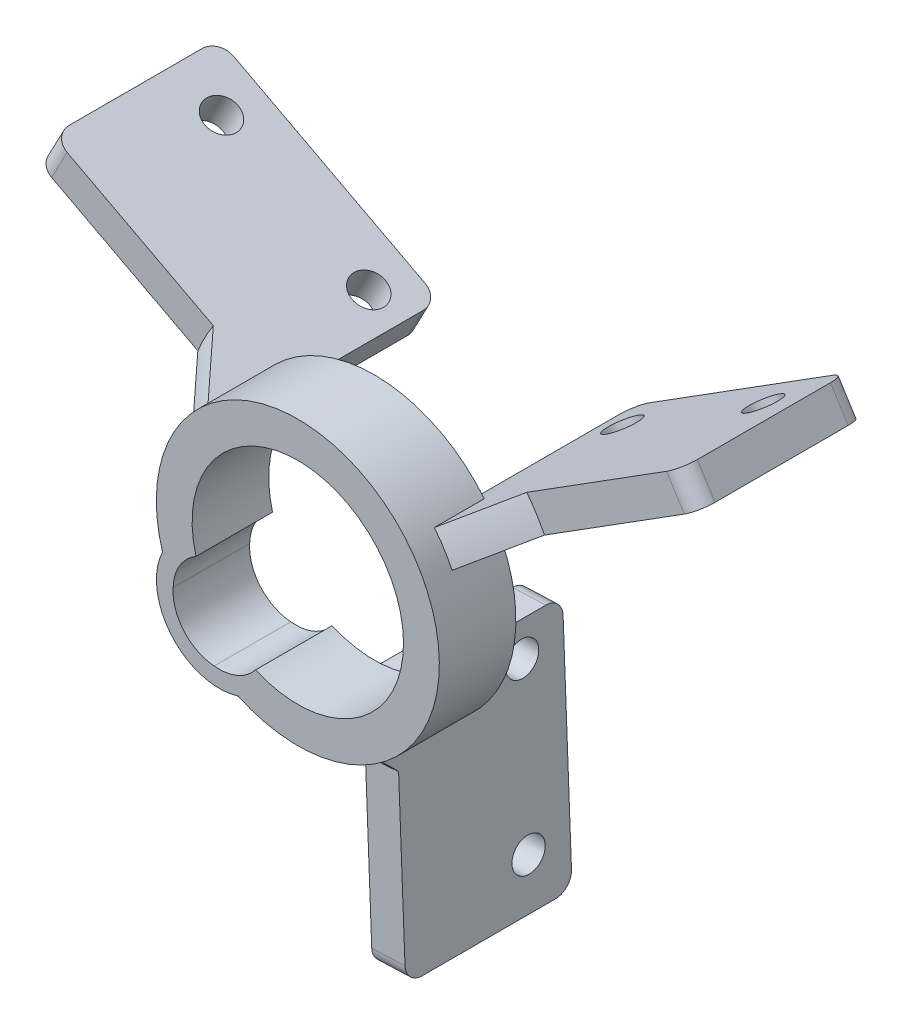
SolidWorks part; units mm, degrees
ref_plane "Alzado" through (0, 0, 0) normal (0, 0, 1) x (1, 0, 0)
ref_plane "Planta" through (0, 0, 0) normal (0, 1, 0) x (1, 0, 0)
ref_plane "Vista lateral" through (0, 0, 0) normal (1, 0, 0) x (0, 0, -1)
sketch "Croquis1" plane through (0, 0, 0) normal (0, 0, 1) x (1, 0, 0)
  circle A1 centre (0, 0) radius 8.5
  dimension "D2" = 17
extrude "Saliente-Extruir1" add sketch "Croquis1" along normal blind 4.6
sketch "Croquis6" plane through (0, 0, 4.6) normal (0, 0, 1) x (1, 0, 0)
  circle A0 centre (0, 0) radius 6.35
  dimension "D1" = 12.7
extrude "Cortar-Extruir1" cut sketch "Croquis6" against normal through all
sketch "Croquis13" plane through (0, 0, 0) normal (0, 0, -1) x (-1, 0, 0)
  circle A0 centre (4.7169, -4.1004) radius 2.775
  circle A1 centre (0, 0) radius 6.35 construction
  arc A2 (1.5517, -6.1575) -> (6.3135, -0.6796) centre (4.7169, -4.1004) ccw
  arc A3 (1.5517, -6.1575) -> (6.3135, -0.6796) centre (0, 0) ccw
  dimension "D1" = 5.55
  dimension "D2" = 6.25
  dimension "D3" = 7.55
extrude "Cortar-Extruir7" cut sketch "Croquis13" against normal blind 10 contours A0
sketch "Croquis14" plane through (0, 0, 0) normal (0, 0, -1) x (-1, 0, 0)
  arc A0 (1.5517, -6.1575) -> (6.3135, -0.6796) centre (4.7169, -4.1004) ccw
  arc A1 (2.5392, -5.8202) -> (5.0208, -6.8587) centre (4.7169, -4.1004) ccw construction
  arc A3 (1.5517, -6.1575) -> (2.5392, -5.8202) centre (0, 0) ccw
  arc A4 (6.117, -1.7044) -> (2.5392, -5.8202) centre (0, 0) ccw construction
  arc A5 (2.5392, -5.8202) -> (5.0208, -6.8587) centre (4.7169, -4.1004) ccw
  arc A6 (6.3135, -0.6796) -> (6.117, -1.7044) centre (0, 0) cw
  arc A7 (6.117, -1.7044) -> (7.4907, -4.0174) centre (4.7169, -4.1004) cw
  arc A8 (7.4907, -4.0174) -> (5.0208, -6.8587) centre (4.8351, -4.2031) cw
  dimension "D1" = 7.55
  dimension "D2" = 0
extrude "Saliente-Extruir4" add sketch "Croquis14" against normal blind 4.6
sketch "Croquis15" plane through (0, 0, 0) normal (0, 0, -1) x (-1, 0, 0)
  line L0 (6.0679, 4.3151) -> (7, 2.5456)
  line L1 (7, 2.5456) -> (20.2714, 9.5363)
  line L2 (20.2714, 9.5363) -> (19.3393, 11.3059)
  line L3 (19.3393, 11.3059) -> (6.0679, 4.3151)
  line L4 (0.1215, -22.4012) -> (0.703, -7.4125)
  line L5 (0.703, -7.4125) -> (-1.2955, -7.335)
  line L6 (-1.2955, -7.335) -> (-1.877, -22.3237)
  line L7 (-1.877, -22.3237) -> (0.1215, -22.4012)
  line L8 (-19.4608, 11.0954) -> (-6.7709, 3.0974)
  line L9 (-6.7709, 3.0974) -> (-5.7045, 4.7894)
  line L10 (-5.7045, 4.7894) -> (-18.3944, 12.7873)
  line L11 (-18.3944, 12.7873) -> (-19.4608, 11.0954)
  point P16 (0, 0)
  dimension "D1" = 2
  dimension "D2" = 15
  dimension "D3" = 7
  dimension "D4" = 4.25
  dimension "D5" = 3
extrude "Saliente-Extruir6" add sketch "Croquis15" along normal blind 10
chamfer "Chaflán1" distance 3 angle 45 1 edges at (-7.5252, 3.9524, 0)
fillet "Redondeo1" radius 1 3 edges at (-19.8053, 10.4211, 0) (-6.5339, 3.4303, -10) (-19.8053, 10.4211, -10)
sketch "Croquis16" plane through (-0.4708, -0.8937, 0) normal (-0.4661, -0.8848, 0) x (-0.8848, 0.4661, 0)
  line L0 (8.3797, 10) -> (21.3797, 10) construction
  line L2 (7.3797, 9) -> (7.3797, 0) construction
  circle A0 centre (9.3797, 7.5) radius 1
  circle A1 centre (19.3797, 7.5) radius 1
  dimension "D1" = 2
  dimension "D2" = 2.5
  dimension "D3" = 2
  dimension "D5" = 10
  dimension "D4" = 2
extrude "Cortar-Extruir8" cut sketch "Croquis16" against normal blind 5
chamfer "Chaflán3" distance 3 angle 45 2 edges at (7.1855, 4.5408, 0) (0.3397, -8.4932, 0)
fillet "Redondeo3" radius 1 6 edges at (6.2377, 3.9434, -10) (0.2962, -7.3737, -10) (0.8777, -22.3625, -10) (0.8777, -22.3625, 0) (18.9276, 11.9414, 0) (18.9276, 11.9414, -10)
sketch "Croquis19" plane through (-0.9891, -0.0384, 0) normal (-0.9992, -0.0388, 0) x (0, 0, 1)
  line L0 (-9, -7.3797) -> (0, -7.3797) construction
  line L1 (-10, -21.3797) -> (-10, -8.3797) construction
  circle A0 centre (-7.5, -9.3797) radius 1
  circle A1 centre (-7.5, -19.3797) radius 1
  dimension "D1" = 2
  dimension "D2" = 2
  dimension "D3" = 2.5
  dimension "D5" = 10
  dimension "D4" = 2
extrude "Cortar-Extruir10" cut sketch "Croquis19" against normal blind 5
sketch "Croquis20" plane through (0.5278, -0.8374, 0) normal (0.5332, -0.846, 0) x (0.846, 0.5332, 0)
  line L0 (7.3797, -9) -> (7.3797, 0) construction
  line L1 (21.3797, -10) -> (8.3797, -10) construction
  circle A0 centre (9.3797, -7.5) radius 1
  circle A1 centre (19.3797, -7.5) radius 1
  dimension "D1" = 2
  dimension "D2" = 2
  dimension "D3" = 2.5
  dimension "D5" = 10
  dimension "D4" = 2
extrude "Cortar-Extruir11" cut sketch "Croquis20" against normal blind 5
